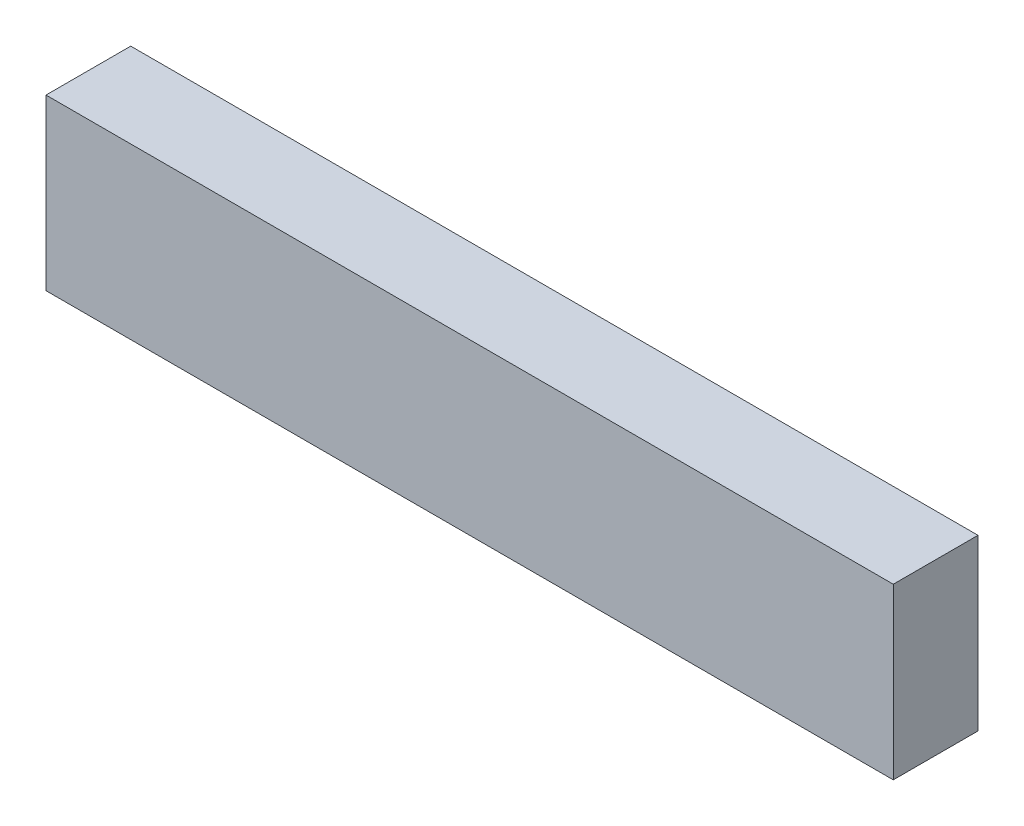
SolidWorks part; units mm, degrees
ref_plane "Front Plane" through (0, 0, 0) normal (0, 0, 1) x (1, 0, 0)
ref_plane "Top Plane" through (0, 0, 0) normal (0, 1, 0) x (1, 0, 0)
ref_plane "Right Plane" through (0, 0, 0) normal (1, 0, 0) x (0, 0, -1)
other "Configuration Table"
sketch "Sketch1" plane through (0, 0, 0) normal (1, 0, 0) x (0, 0, -1)
  line L0 (0, 55) -> (0, -55) construction
  line L1 (0, 32.8388) -> (-1000, 32.8388)
  line L2 (0, 32.8388) -> (0, -1967.1612)
  line L3 (0, -1967.1612) -> (-1000, -1967.1612)
  line L4 (-1000, 32.8388) -> (-1000, -1967.1612)
  dimension "D1" = 1000
  dimension "D2" = 2000
extrude "Extrude1" add sketch "Sketch1" along normal blind 10000
